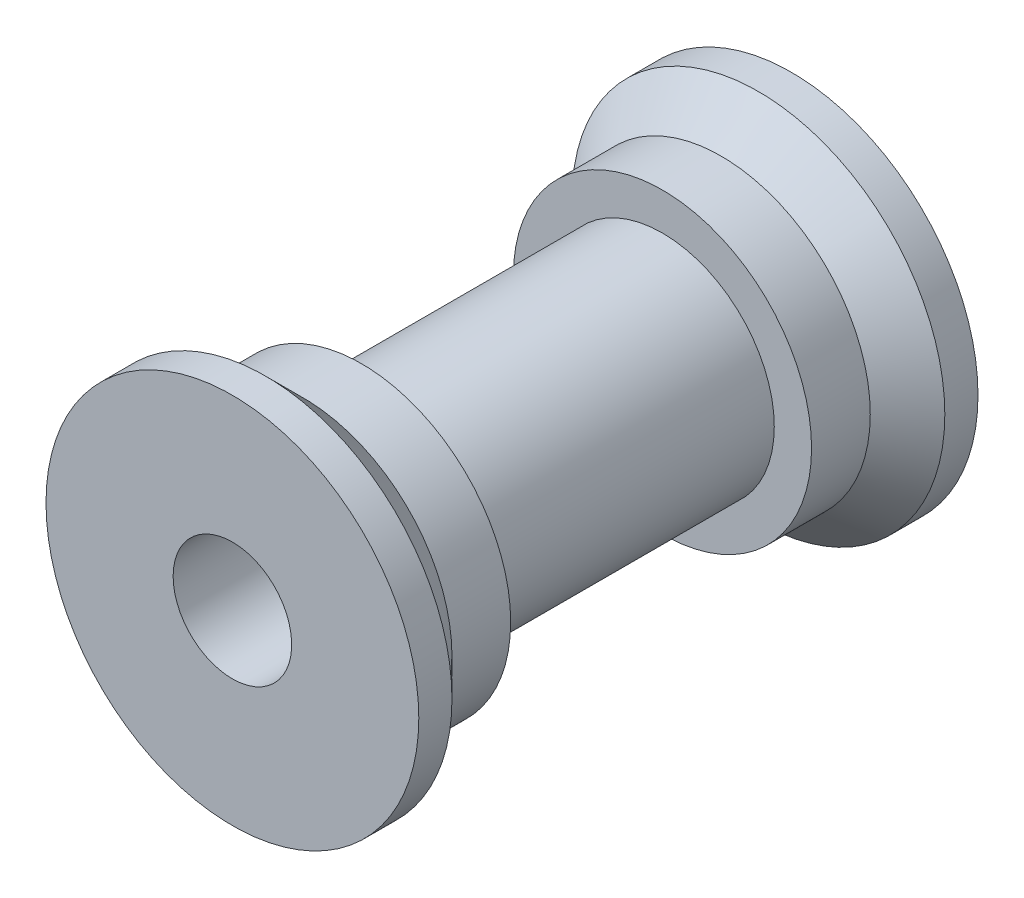
SolidWorks part; units mm, degrees
ref_plane "Front Plane" through (0, 0, 0) normal (0, 0, 1) x (1, 0, 0)
ref_plane "Top Plane" through (0, 0, 0) normal (0, 1, 0) x (1, 0, 0)
ref_plane "Right Plane" through (0, 0, 0) normal (1, 0, 0) x (0, 0, -1)
sketch "Sketch1" plane through (0, 0, 0) normal (0, 0, 1) x (1, 0, 0)
  circle A0 centre (0, 0) radius 12.7
  circle A1 centre (0, 0) radius 4.0386
extrude "Boss-Extrude1" add sketch "Sketch1" along normal blind 38.1
sketch "Sketch2" plane through (0, 0, 0) normal (0, 1, 0) x (1, 0, 0)
  line L0 (10.16, -33.3) -> (12.7, -35.84)
  line L1 (10.16, -4.8) -> (12.7, -2.26)
  line L4 (12.7, -38.1) -> (12.7, 0) construction
  line L5 (12.7, -35.84) -> (12.7, -2.26)
  line L6 (0, 0) -> (0, -38.1) construction
  line L8 (10.16, -33.3) -> (10.16, -29.3)
  line L9 (10.16, -29.3) -> (7.62, -29.3)
  line L10 (7.62, -29.3) -> (7.62, -8.8)
  line L11 (7.62, -8.8) -> (10.16, -8.8)
  line L12 (10.16, -8.8) -> (10.16, -4.8)
  line L13 (-12.7, -38.1) -> (12.7, -38.1) construction
revolve "Cut-Revolve1" cut sketch "Sketch2" angle 360 about L6
